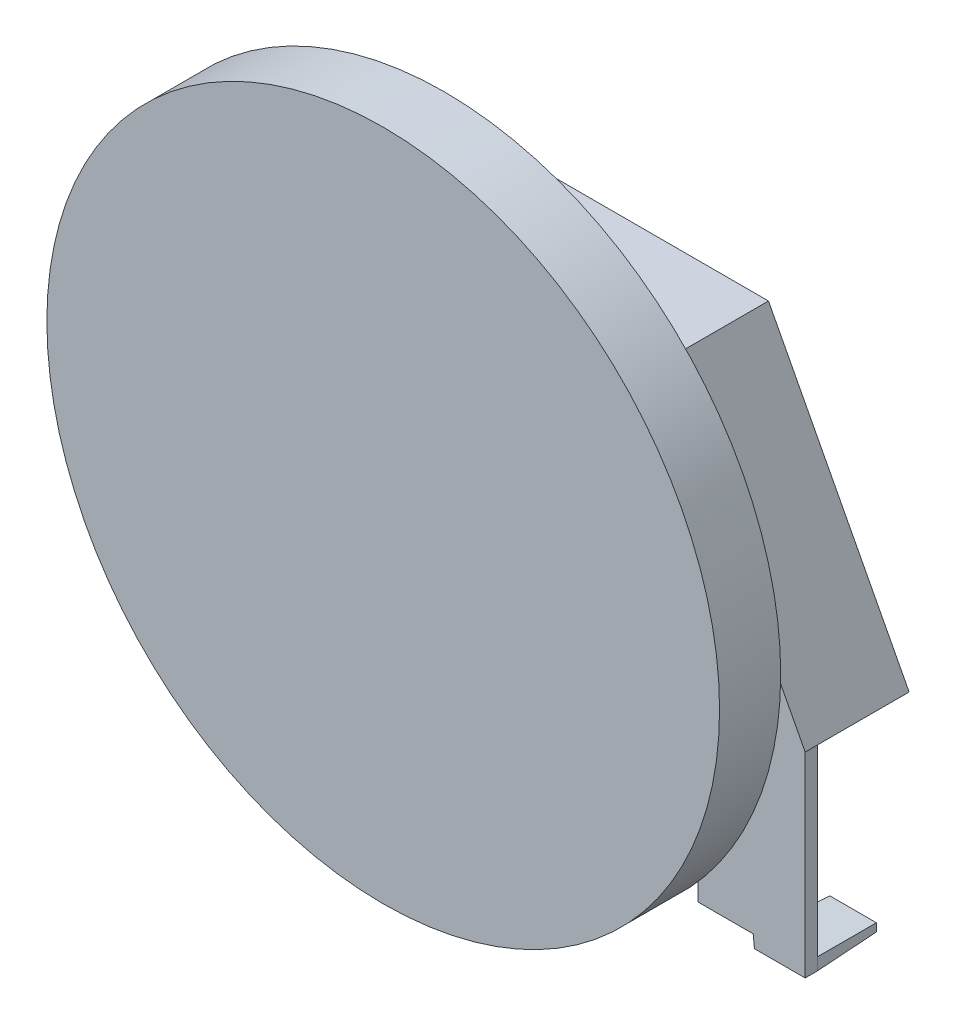
SolidWorks part; units mm, degrees
ref_plane "Front Plane" through (0, 0, 0) normal (0, 0, 1) x (1, 0, 0)
ref_plane "Top Plane" through (0, 0, 0) normal (0, 1, 0) x (1, 0, 0)
ref_plane "Right Plane" through (0, 0, 0) normal (1, 0, 0) x (0, 0, -1)
sketch "Sketch1" plane through (0, 0, 0) normal (0, 0, 1) x (1, 0, 0)
  circle A0 centre (0, 0) radius 11
  dimension "D1" = 22
extrude "Boss-Extrude1" add sketch "Sketch1" along normal blind 2
sketch "Sketch2" plane through (0, 0, 0) normal (0, 0, -1) x (-1, 0, 0)
  circle A0 centre (0, 0) radius 7
  dimension "D1" = 14
extrude "Boss-Extrude2" add sketch "Sketch2" along normal blind 2.2
sketch "Sketch3" plane through (0, 0, -2.2) normal (0, 0, -1) x (-1, 0, 0)
  circle A0 centre (0, 0) radius 5.5
  dimension "D1" = 11
extrude "Boss-Extrude3" add sketch "Sketch3" along normal blind 1
sketch "Sketch4" plane through (0, 0, -3.2) normal (0, 0, -1) x (-1, 0, 0)
  line L0 (-4, 3.7749) -> (4, 3.7749)
  line L1 (4, 3.7749) -> (8.6, -5)
  line L2 (8.6, -5) -> (8.6, -18)
  line L3 (8.6, -18) -> (7.6, -18)
  line L4 (7.6, -18) -> (6.9, -11)
  line L5 (6.9, -11) -> (5.1, -11)
  line L6 (5.1, -11) -> (5.1, -2.0591)
  line L7 (5.1, -2.0591) -> (3.85, -2.0591)
  line L8 (0, -5.5) -> (0, 3.7749) construction
  line L9 (3.85, -2.0591) -> (3.5, -18)
  line L10 (3.5, -18) -> (2.5, -18)
  line L11 (2.5, -18) -> (2.15, -2.0591)
  line L12 (2.15, -2.0591) -> (0.85, -2.0591)
  line L13 (0.85, -2.0591) -> (0.5, -18)
  line L14 (0.5, -18) -> (-0.5, -18)
  line L15 (-0.85, -2.0591) -> (-0.5, -18)
  line L16 (-2.15, -2.0591) -> (-0.85, -2.0591)
  line L17 (-2.5, -18) -> (-2.15, -2.0591)
  line L18 (-3.5, -18) -> (-2.5, -18)
  line L19 (-3.85, -2.0591) -> (-3.5, -18)
  line L20 (-5.1, -2.0591) -> (-3.85, -2.0591)
  line L21 (-5.1, -11) -> (-5.1, -2.0591)
  line L22 (-6.9, -11) -> (-5.1, -11)
  line L23 (-7.6, -18) -> (-6.9, -11)
  line L24 (-8.6, -18) -> (-7.6, -18)
  line L25 (-8.6, -5) -> (-8.6, -18)
  line L26 (-4, 3.7749) -> (-8.6, -5)
  circle A0 centre (0, 0) radius 5.5 construction
  circle A1 centre (0, 0) radius 5.5 construction
  point P21 (0, -18)
  point P34 (3.5612, -18)
  point P35 (4.2931, -8.8599)
  point P36 (2.7673, -18)
  point P37 (3.7673, -8.7687)
  point P38 (0, 0)
  point P39 (2.3489, -8.7864)
  point P40 (4, -8.7621)
  point P41 (3, -18)
  point P42 (5.1, -2.0591)
  dimension "D1" = 13
  dimension "D2" = 1
  dimension "D3" = 3.5
  dimension "D4" = 1.7
  dimension "D5" = 8
  dimension "D6" = 5
  dimension "D7" = 17.2
  dimension "D8" = 1.7
  dimension "D9" = 1.7
  dimension "D10" = 3
  dimension "D11" = 7
extrude "Boss-Extrude4" add sketch "Sketch4" along normal blind 0.4
sketch "Sketch5" plane through (0, 0, -3.6) normal (0, 0, -1) x (-1, 0, 0)
  line L0 (-8.6, -5) -> (-4, 3.7749)
  line L1 (-4, 3.7749) -> (4, 3.7749)
  line L2 (4, 3.7749) -> (-4, 3.7749) construction
  line L3 (4, 3.7749) -> (8.6, -5)
  line L4 (8.6, -5) -> (-8.6, -5)
  line L5 (5.3801, 1.1423) -> (4, 3.7749) construction
  circle A0 centre (0, 0) radius 5.5 construction
  point P4 (4, 3.7749)
extrude "Boss-Extrude5" add sketch "Sketch5" along normal blind 3
sketch "Sketch6" plane through (0, 0, -3.6) normal (0, 0, -1) x (-1, 0, 0)
  line L0 (8.6, -18) -> (8.6, -5) construction
  line L1 (8.6, -11.4) -> (6.94, -11.4)
  line L2 (8.6, -11.4) -> (8.6, -11)
  line L3 (8.6, -11) -> (6.94, -11)
  line L4 (6.94, -11.4) -> (6.94, -11)
  line L5 (5.1, -11) -> (6.9, -11) construction
  line L6 (6.9, -11) -> (7.6, -18) construction
  line L8 (0, 0) -> (0, -5) construction
  line L9 (2.3551, -11) -> (3.6449, -11)
  line L10 (2.3551, -11) -> (2.3551, -11.4)
  line L11 (2.3551, -11.4) -> (3.6449, -11.4)
  line L12 (3.6449, -11) -> (3.6449, -11.4)
  line L13 (-0.6449, -11) -> (0.6449, -11)
  line L14 (-0.6449, -11) -> (-0.6449, -11.4)
  line L15 (-0.6449, -11.4) -> (0.6449, -11.4)
  line L16 (0.6449, -11) -> (0.6449, -11.4)
  line L17 (-0.7854, -5) -> (0.7854, -5) construction
  line L18 (-3.6449, -11) -> (-3.6449, -11.4)
  line L19 (-2.3551, -11.4) -> (-3.6449, -11.4)
  line L20 (-2.3551, -11) -> (-2.3551, -11.4)
  line L21 (-2.3551, -11) -> (-3.6449, -11)
  line L22 (-6.94, -11.4) -> (-6.94, -11)
  line L23 (-8.6, -11) -> (-6.94, -11)
  line L24 (-8.6, -11.4) -> (-8.6, -11)
  line L25 (-8.6, -11.4) -> (-6.94, -11.4)
  line L26 (3.5, -18) -> (3.7854, -5) construction
  line L27 (2.2146, -5) -> (2.5, -18) construction
  line L28 (0.5, -18) -> (0.7854, -5) construction
  line L29 (-0.7854, -5) -> (-0.5, -18) construction
  point P31 (3.6449, -11.4)
  point P34 (2.3551, -11.4)
  point P37 (0.6449, -11.4)
  point P40 (-0.6449, -11.4)
  dimension "D1" = 0.4
extrude "Boss-Extrude6" add sketch "Sketch6" along normal blind 2 draft 2
sketch "Sketch7" plane through (0, 0, -3.6) normal (0, 0, -1) x (-1, 0, 0)
  line L1 (-8.6, -11.4) -> (8.6, -11.4)
  line L2 (-8.6, -11.4) -> (-8.6, -18)
  line L3 (-8.6, -18) -> (8.6, -18)
  line L4 (8.6, -11.4) -> (8.6, -18)
  point P5 (8.6, -11.4)
  point P7 (8.6, -18)
extrude "Cut-Extrude1" cut sketch "Sketch7" against normal blind 2
